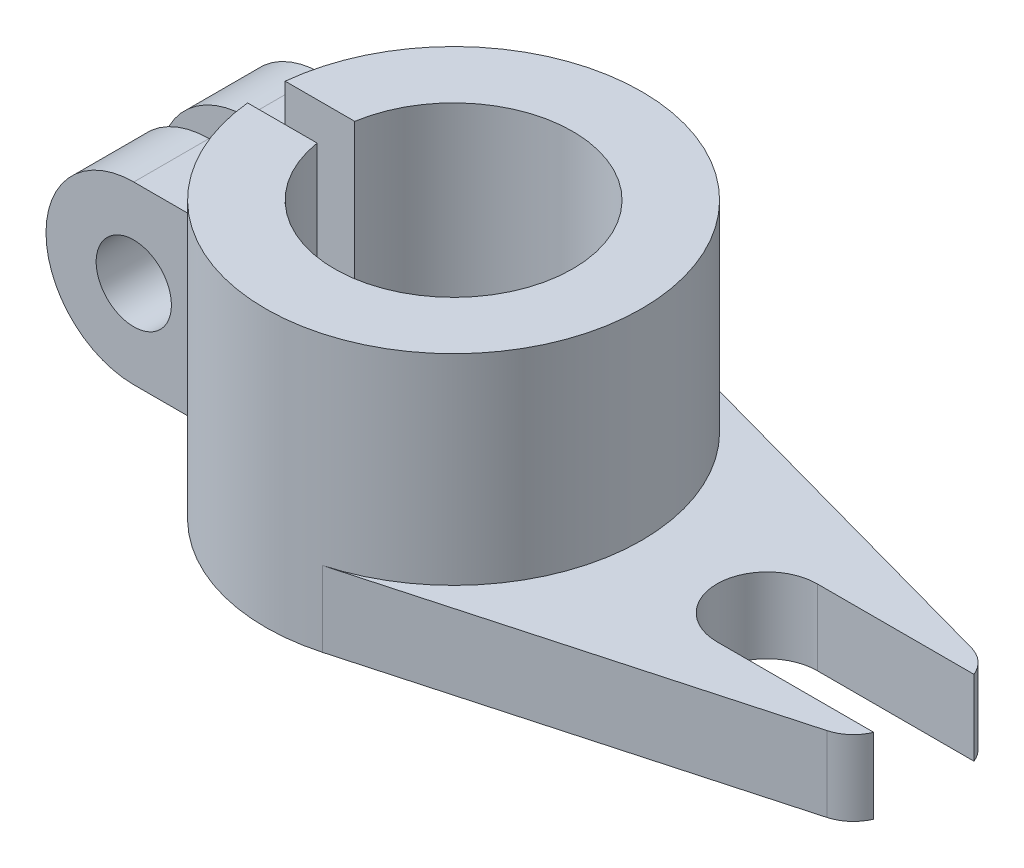
SolidWorks part; units mm, degrees
ref_plane "Front Plane" through (0, 0, 0) normal (0, 0, 1) x (1, 0, 0)
ref_plane "Top Plane" through (0, 0, 0) normal (0, 1, 0) x (1, 0, 0)
ref_plane "Right Plane" through (0, 0, 0) normal (1, 0, 0) x (0, 0, -1)
sketch "Sketch1" plane through (0, 0, 0) normal (0, 1, 0) x (1, 0, 0)
  line L0 (0, 0) -> (105.1836, 0) construction
  line L1 (0, 0) -> (0, 81.5173) construction
  circle A0 centre (0, 0) radius 30
extrude "Boss-Extrude1" add sketch "Sketch1" along normal blind 44
sketch "Sketch2" plane through (0, 0, 0) normal (0, 1, 0) x (1, 0, 0)
  line L0 (0, 0) -> (50, 0) construction
  line L1 (50, 0) -> (75, 0) construction
  line L2 (50, 8) -> (75, 8)
  line L3 (50, -8) -> (75, -8)
  line L4 (7.9919, 28.9159) -> (71.0555, 11.4861)
  line L5 (7.9919, -28.9159) -> (71.0555, -11.4861)
  arc A0 (50, 8) -> (50, -8) centre (50, 0) ccw
  arc A1 (75, 8) -> (71.0555, 11.4861) centre (69.4571, 5.703) ccw
  circle A2 centre (0, 0) radius 30 construction
  arc A4 (75, -8) -> (71.0555, -11.4861) centre (69.4571, -5.703) cw
  arc A5 (7.9919, 28.9159) -> (7.9919, -28.9159) centre (0, 0) cw
  dimension "D1" = 50
  dimension "D2" = 25
extrude "Boss-Extrude2" add sketch "Sketch2" along normal blind 12
sketch "Sketch3" plane through (0, 0, 0) normal (0, 0, 1) x (1, 0, 0)
  line L0 (0, 0) -> (-50, 0) construction
  line L1 (-50, 0) -> (-50, 22) construction
  line L2 (-50, 22) -> (-36, 22) construction
  line L3 (-36, 36) -> (-23.9015, 36)
  line L5 (-36, 8) -> (-23.9015, 8)
  line L6 (-23.9015, 36) -> (-23.9015, 8)
  arc A0 (-36, 36) -> (-36, 8) centre (-36, 22) ccw
  circle A1 centre (-36, 22) radius 6
  dimension "D4" = 12
  dimension "D1" = 50
  dimension "D2" = 22
  dimension "D3" = 14
extrude "Boss-Extrude3" add sketch "Sketch3" along normal mid plane 30 contours A0 L5 L6 L3
sketch "Sketch4" plane through (0, 0, 0) normal (0, 1, 0) x (1, 0, 0)
  line L0 (-19, 0) -> (-72.566, 0) construction
  line L1 (-72.566, 0) -> (-72.566, 3)
  line L2 (-72.566, 3) -> (-18.7617, 3)
  line L5 (-18.7617, -3) -> (-72.566, -3)
  line L6 (-72.566, -3) -> (-72.566, 0)
  arc A0 (-18.7617, -3) -> (-18.7617, 3) centre (0, 0) ccw
  point P3 (0, 0)
  point P9 (0, 0)
  dimension "D1" = 6
extrude "Cut-Extrude1" cut sketch "Sketch4" along normal through all
sketch "Sketch5" plane through (0, 0, 15) normal (0, 0, 1) x (1, 0, 0)
  circle A0 centre (-36, 22) radius 6
extrude "Cut-Extrude2" cut sketch "Sketch5" against normal through all
